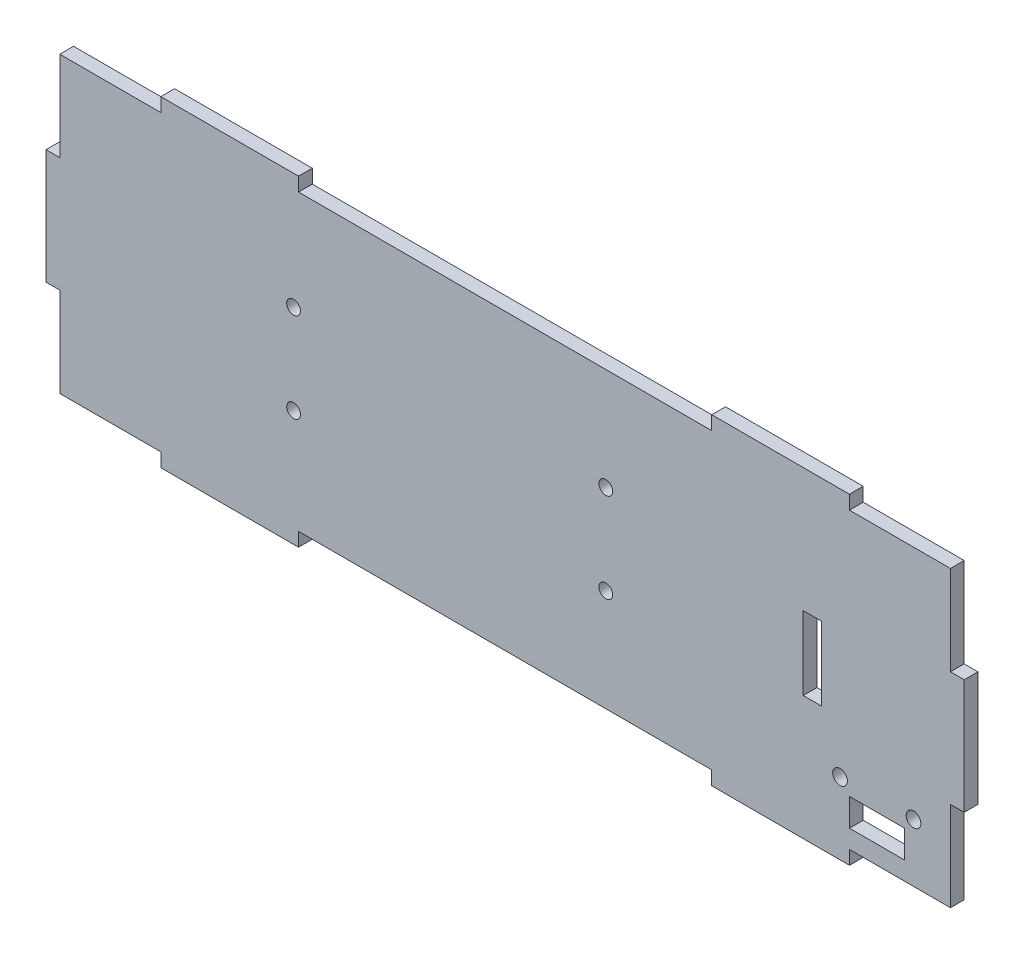
SolidWorks part; units mm, degrees
ref_plane "Alzado" through (0, 0, 0) normal (0, 0, 1) x (1, 0, 0)
ref_plane "Planta" through (0, 0, 0) normal (0, 1, 0) x (1, 0, 0)
ref_plane "Vista lateral" through (0, 0, 0) normal (1, 0, 0) x (0, 0, -1)
sketch "Croquis1" plane through (0, 0, 0) normal (0, 0, 1) x (1, 0, 0)
  line L0 (0, 35) -> (0, -35) construction
  line L1 (-100, -35) -> (100, -35)
  line L2 (-100, -35) -> (-100, 35)
  line L3 (-100, 35) -> (100, 35)
  line L4 (100, -35) -> (100, 35)
  line L5 (-100, -35) -> (100, 35) construction
  line L6 (-100, 35) -> (100, -35) construction
  line L7 (-100, 35) -> (-97, 35)
  line L8 (-100, 35) -> (-100, 12.5)
  line L9 (-100, 12.5) -> (-97, 12.5)
  line L10 (-97, 35) -> (-97, 12.5)
  line L11 (-100, -35) -> (-97, -35)
  line L12 (-100, -35) -> (-100, -12.5)
  line L13 (-100, -12.5) -> (-97, -12.5)
  line L14 (-97, -35) -> (-97, -12.5)
  line L15 (-100, -32) -> (-75, -32)
  line L16 (-100, -32) -> (-100, -35)
  line L17 (-100, -35) -> (-75, -35)
  line L18 (-75, -32) -> (-75, -35)
  line L19 (-45, -32) -> (45, -32)
  line L20 (-45, -32) -> (-45, -35)
  line L21 (-45, -35) -> (45, -35)
  line L22 (45, -32) -> (45, -35)
  line L23 (100, -35) -> (75, -35)
  line L24 (100, -35) -> (100, -32)
  line L25 (100, -32) -> (75, -32)
  line L26 (75, -35) -> (75, -32)
  line L27 (-100, 0) -> (100, 0) construction
  line L28 (-75, 32) -> (-75, 35)
  line L29 (-100, 32) -> (-75, 32)
  line L30 (45, 32) -> (45, 35)
  line L31 (75, 35) -> (75, 32)
  line L32 (100, 32) -> (75, 32)
  line L33 (-45, 32) -> (-45, 35)
  line L34 (-45, 32) -> (45, 32)
  line L35 (97, -35) -> (97, -12.5)
  line L36 (100, -12.5) -> (97, -12.5)
  line L37 (100, 12.5) -> (97, 12.5)
  line L38 (97, 35) -> (97, 12.5)
  point P0 (0, 0)
  point P24 (0, -32)
  dimension "D1" = 200
  dimension "D2" = 70
  dimension "D3" = 25
  dimension "D4" = 3
  dimension "D6" = 30
  dimension "D7" = 30
  dimension "D8" = 45
  dimension "D9" = 3
extrude "Saliente-Extruir1" add sketch "Croquis1" along normal mid plane 3 contours L38 L32 L31 L3 L30 L34 L33 L28 L29 L10 L9 L2 L13 L14 L15 L18 L1 L20 L19 L22 L26 L25 L35 L36 L4 L37
sketch "Croquis2" plane through (0, 0, 1.5) normal (0, 0, 1) x (1, 0, 0)
  line L0 (72.9486, -19.3545) -> (88.9486, -19.3545) construction
  line L1 (0, 30.2735) -> (0, -53.331) construction
  line L2 (0, 0) -> (121.1352, 0) construction
  circle A0 centre (72.9486, -19.3545) radius 1.6
  circle A1 centre (88.9486, -19.3545) radius 1.6
  point P9 (80.9486, -19.3545)
  dimension "D4" = 3.2
  dimension "D1" = 80.9486
  dimension "D2" = 16
  dimension "D3" = 19.3545
extrude "Cortar-Extruir1" cut sketch "Croquis2" against normal blind 10
sketch "Croquis3" plane through (0, 0, 1.5) normal (0, 0, 1) x (1, 0, 0)
  line L0 (0, 51.7966) -> (0, -71.6683) construction
  line L1 (75, -28) -> (87, -28)
  line L2 (75, -28) -> (75, -22)
  line L3 (75, -22) -> (87, -22)
  line L4 (87, -28) -> (87, -22)
  line L5 (75, -28) -> (87, -22) construction
  line L6 (75, -22) -> (87, -28) construction
  line L7 (0, 0) -> (177.0165, 0) construction
  point P0 (81, -25)
  dimension "D1" = 6
  dimension "D2" = 12
  dimension "D3" = 25
  dimension "D4" = 81
extrude "Cortar-Extruir2" cut sketch "Croquis3" against normal blind 10
sketch "Croquis4" plane through (0, 0, 1.5) normal (0, 0, 1) x (1, 0, 0)
  line L0 (0, 0) -> (145.3042, 0) construction
  line L1 (0, 61.0299) -> (0, -57.6644) construction
  line L2 (66.93, 18.0834) -> (66.93, -20.3411) construction
  line L5 (64.93, -8) -> (68.93, -8)
  line L6 (64.93, -8) -> (64.93, 8)
  line L7 (64.93, 8) -> (68.93, 8)
  line L8 (68.93, -8) -> (68.93, 8)
  line L9 (64.93, -8) -> (68.93, 8) construction
  line L10 (64.93, 8) -> (68.93, -8) construction
  point P9 (66.93, 0)
  dimension "D2" = 4
  dimension "D3" = 16
  dimension "D4" = 66.93
extrude "Cortar-Extruir3" cut sketch "Croquis4" against normal blind 10
sketch "Croquis5" plane through (0, 0, 1.5) normal (0, 0, 1) x (1, 0, 0)
  line L0 (-100, 0) -> (100, 0) construction
  line L1 (-100, -12.5) -> (-100, 12.5) construction
  line L2 (100, -12.5) -> (100, 12.5) construction
  line L3 (-12.07, 32) -> (-12.07, -32) construction
  line L4 (-45, 32) -> (45, 32) construction
  line L5 (-45, -32) -> (45, -32) construction
  line L6 (64.93, 8) -> (64.93, -8) construction
  circle A0 centre (21.93, 9.75) radius 1.5
  circle A1 centre (21.93, -9.75) radius 1.5
  circle A2 centre (-46.07, -9.75) radius 1.5
  circle A3 centre (-46.07, 9.75) radius 1.5
  dimension "D1" = 3
  dimension "D4" = 34
  dimension "D2" = 9.75
  dimension "D3" = 43
extrude "Cortar-Extruir4" cut sketch "Croquis5" against normal up to next
